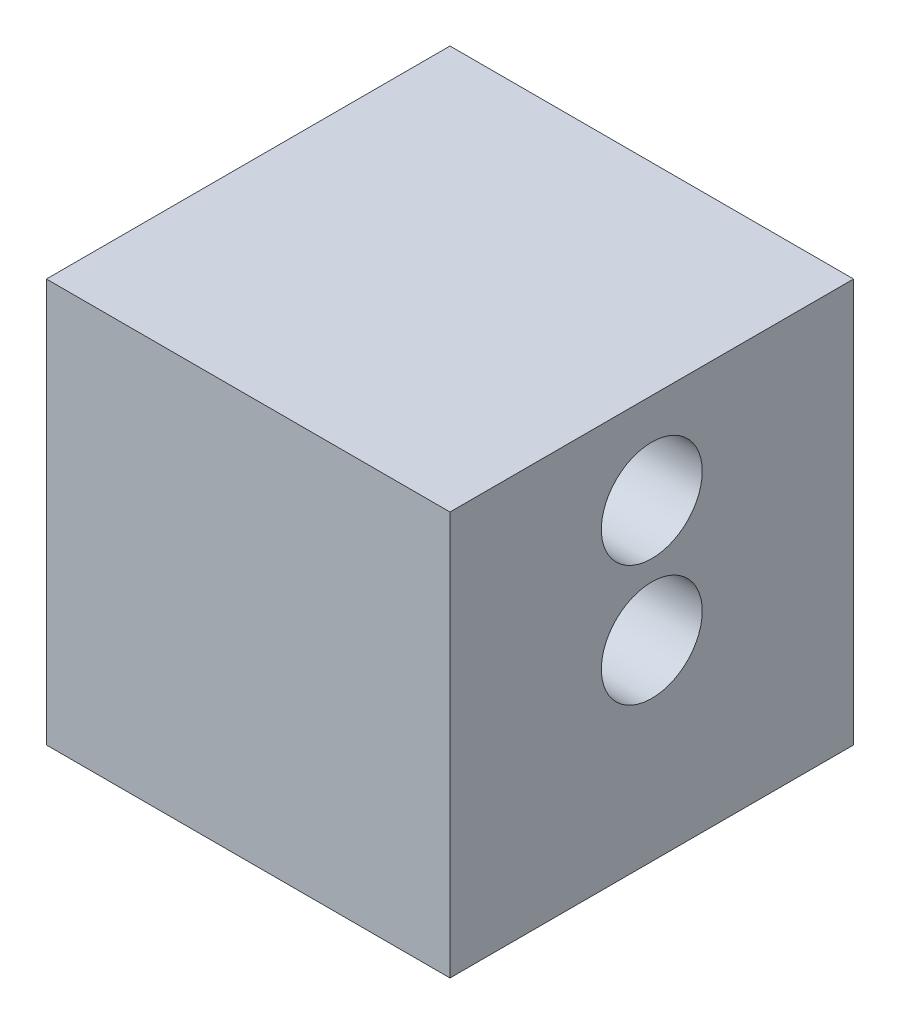
SolidWorks part; units mm, degrees
ref_plane "Front Plane" through (0, 0, 0) normal (0, 0, 1) x (1, 0, 0)
ref_plane "Top Plane" through (0, 0, 0) normal (0, 1, 0) x (1, 0, 0)
ref_plane "Right Plane" through (0, 0, 0) normal (1, 0, 0) x (0, 0, -1)
sketch "Sketch1" plane through (0, 0, 0) normal (0, 1, 0) x (1, 0, 0)
  line L1 (0, 0) -> (-20, 0)
  line L2 (0, 0) -> (0, 20)
  line L3 (0, 20) -> (-20, 20)
  line L4 (-20, 0) -> (-20, 20)
  dimension "D1" = 20
  dimension "D2" = 20
extrude "Boss-Extrude1" add sketch "Sketch1" along normal blind 20
sketch "Sketch3" plane through (0, 0, 0) normal (1, 0, 0) x (0, 0, -1)
  line L0 (0, 20) -> (0, 0) construction
  line L2 (10, 18) -> (11.5875, 18) construction
  line L3 (0, 20) -> (20, 20) construction
  circle A0 centre (10, 15.5) radius 2.5
  dimension "D3" = 5
  dimension "D1" = 10
  dimension "D2" = 2
extrude "Cut-Extrude1" cut sketch "Sketch3" against normal through all
sketch "Sketch4" plane through (0, 0, 0) normal (1, 0, 0) x (0, 0, -1)
  line L0 (0, 20) -> (0, 0) construction
  line L1 (10, 7) -> (13.4988, 7) construction
  line L2 (0, 0) -> (20, 0) construction
  circle A0 centre (10, 9.5) radius 2.5
  dimension "D2" = 5
  dimension "D1" = 10
  dimension "D3" = 7
extrude "Cut-Extrude2" cut sketch "Sketch4" against normal blind 15 contours A0
